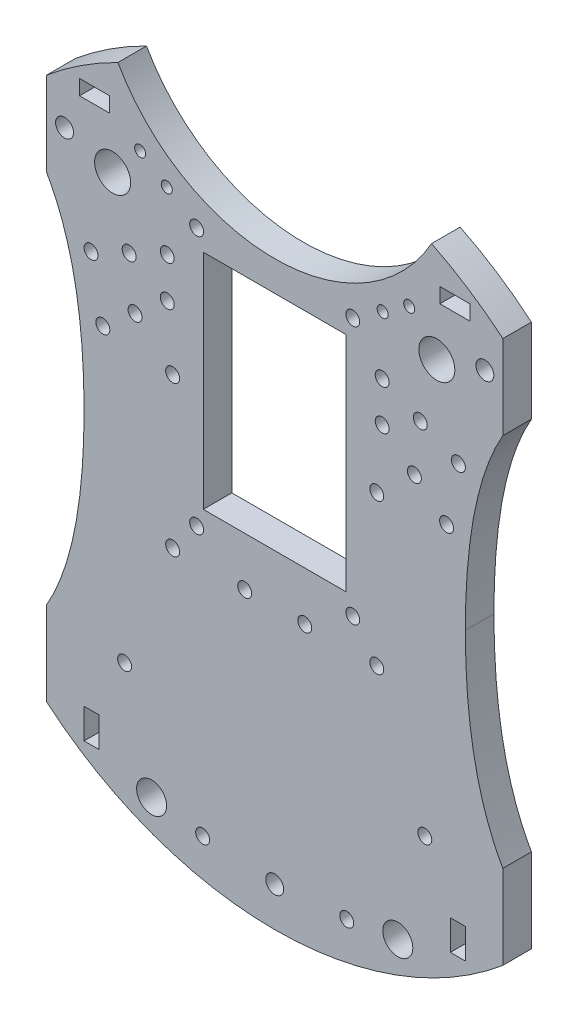
SolidWorks part; units mm, degrees
ref_plane "Front Plane" through (0, 0, 0) normal (0, 0, 1) x (1, 0, 0)
ref_plane "Top Plane" through (0, 0, 0) normal (0, 1, 0) x (1, 0, 0)
ref_plane "Right Plane" through (0, 0, 0) normal (1, 0, 0) x (0, 0, -1)
sketch "Sketch1" plane through (0, 0, 0) normal (0, 0, 1) x (1, 0, 0)
  line L0 (0, 47.9049) -> (0, -75) construction
  line L1 (-48.26, 0) -> (48.26, 0) construction
  line L5 (-48.26, 57.4106) -> (-48.26, -57.4106)
  line L22 (48.26, 57.4106) -> (48.26, -57.4106)
  arc A0 (-33.1727, 67.265) -> (-48.26, 57.4106) centre (0, 0) ccw
  arc A1 (-33.1727, 67.265) -> (33.1727, 67.265) centre (0, 86.0049) ccw
  circle A2 centre (0, -66.675) radius 1.8987
  circle A3 centre (-44.45, 49.6966) radius 1.8987
  circle A4 centre (44.45, 49.6966) radius 1.8986
  circle A5 centre (-21.59, -15.875) radius 1.4732
  circle A6 centre (-6.35, -15.875) radius 1.4732
  circle A7 centre (6.35, -15.875) radius 1.4732
  circle A8 centre (-15.24, -65.475) radius 1.4732
  circle A9 centre (15.24, -65.475) radius 1.4732
  circle A12 centre (21.59, -15.875) radius 1.4732
  circle A13 centre (6.35, 15.875) radius 1.4732
  circle A14 centre (-6.35, 15.875) radius 1.4732
  circle A15 centre (21.59, 15.875) radius 1.4732
  circle A18 centre (-21.59, 15.875) radius 1.4732
  arc A29 (-48.26, -57.4106) -> (48.26, -57.4106) centre (0, 0) ccw
  arc A30 (48.26, 57.4106) -> (33.1727, 67.265) centre (0, 0) ccw
  circle A31 centre (0, 0) radius 66.675 construction
  point P1 (-48.26, 0)
  point P50 (0, -65.475)
  dimension "D1" = 150
  dimension "D8" = 3.7973
  dimension "D12" = 133.35
  dimension "D11" = 3.7973
  dimension "D20" = 26.67
  dimension "D19" = 2.9464
  dimension "D9" = 2.9464
  dimension "D2" = 66.3453
  dimension "D3" = 38.1
  dimension "D4" = 44.45
  dimension "D6" = 48.26
  dimension "D7" = 0
  dimension "D13" = 15.875
  dimension "D14" = 9.525
  dimension "D18" = 0
  dimension "D23" = 15.24
  dimension "D10" = 15.24
extrude "Boss-Extrude3" add sketch "Sketch1" along normal blind 6.0452
sketch "Sketch7" plane through (0, 0, 6.0452) normal (0, 0, 1) x (1, 0, 0)
  line L0 (-34.925, -41.98) -> (34.925, -41.98) construction
  line L1 (-34.925, -61.03) -> (-34.925, -22.93) construction
  line L2 (-34.925, -61.03) -> (34.925, -61.03) construction
  line L3 (34.925, -61.03) -> (34.925, -22.93) construction
  line L4 (-34.925, -22.93) -> (34.925, -22.93) construction
  line L5 (0, -61.03) -> (0, -22.93) construction
  line L6 (-28.575, -55.7849) -> (-28.575, -28.1751) construction
  line L7 (-28.575, -55.7849) -> (28.575, -55.7849) construction
  line L8 (28.575, -55.7849) -> (28.575, -28.1751) construction
  line L9 (-28.575, -28.1751) -> (28.575, -28.1751) construction
  line L10 (-28.575, -55.7849) -> (28.575, -28.1751) construction
  line L11 (28.575, -55.7849) -> (-28.575, -28.1751) construction
  line L12 (0, 47.9049) -> (0, -75) construction
  circle A0 centre (-31.75, -41.98) radius 1.4732
  circle A1 centre (31.75, -41.98) radius 1.4732
  arc A2 (-33.1727, 67.265) -> (33.1727, 67.265) centre (0, 86.0049) ccw construction
  arc A3 (-48.26, -57.4106) -> (48.26, -57.4106) centre (0, 0) ccw construction
  point P0 (0, -41.98)
  dimension "D1" = 69.85
  dimension "D2" = 57.15
  dimension "D3" = 27.6098
  dimension "D4" = 3.175
  dimension "D5" = 38.1
  dimension "D6" = 33.02
extrude "Cut-Extrude2" cut sketch "Sketch7" against normal through all
sketch "Sketch9" plane through (0, 0, 6.0452) normal (0, 0, 1) x (1, 0, 0)
  line L1 (-15.113, 41.5549) -> (15.113, 41.5549)
  line L2 (-15.113, 41.5549) -> (-15.113, -5.5621)
  line L3 (-15.113, -5.5621) -> (15.113, -5.5621)
  line L4 (15.113, 41.5549) -> (15.113, -5.5621)
  line L5 (-15.113, 17.9964) -> (15.113, 17.9964) construction
  line L6 (0, 47.8414) -> (0, -11.8486) construction
  line L7 (0, 47.9049) -> (0, -75) construction
  line L8 (-19.05, 47.8414) -> (19.05, 47.8414) construction
  line L9 (-19.05, 47.8414) -> (-19.05, -11.8486) construction
  line L10 (-19.05, -11.8486) -> (19.05, -11.8486) construction
  line L11 (19.05, 47.8414) -> (19.05, -11.8486) construction
  line L12 (-19.05, 17.9964) -> (19.05, 17.9964) construction
  arc A1 (-33.1727, 67.265) -> (33.1727, 67.265) centre (0, 86.0049) ccw construction
  arc A2 (-48.26, -57.4106) -> (48.26, -57.4106) centre (0, 0) ccw construction
  circle A3 centre (-16.51, 45.3014) radius 1.4732
  circle A4 centre (16.51, 45.3014) radius 1.4732
  circle A5 centre (-16.51, -9.3086) radius 1.4732
  circle A6 centre (16.51, -9.3086) radius 1.4732
  point P6 (0, 17.9964)
  dimension "D6" = 2.9464
  dimension "D7" = 5.08
  dimension "D8" = 5.08
  dimension "D1" = 30.226
  dimension "D2" = 47.117
  dimension "D3" = 6.35
  dimension "D4" = 59.69
  dimension "D5" = 38.1
extrude "Cut-Extrude3" cut sketch "Sketch9" against normal blind 14.732
sketch "Sketch10" plane through (0, 0, 6.0452) normal (0, 0, 1) x (1, 0, 0)
  line L0 (0, 47.9049) -> (0, -75) construction
  line L2 (-41.275, 60.2874) -> (-34.925, 60.2874)
  line L3 (-41.275, 60.2874) -> (-41.275, 57.1124)
  line L4 (-41.275, 57.1124) -> (-34.925, 57.1124)
  line L5 (-34.925, 60.2874) -> (-34.925, 57.1124)
  line L6 (-41.275, 60.2874) -> (-34.925, 57.1124) construction
  line L7 (-41.275, 57.1124) -> (-34.925, 60.2874) construction
  line L8 (34.925, 60.2874) -> (34.925, 57.1124)
  line L9 (41.275, 60.2874) -> (34.925, 60.2874)
  line L10 (41.275, 60.2874) -> (41.275, 57.1124)
  line L11 (41.275, 57.1124) -> (34.925, 57.1124)
  line L13 (-40.3225, -54.2356) -> (-37.1475, -54.2356)
  line L14 (-40.3225, -54.2356) -> (-40.3225, -60.5856)
  line L15 (-40.3225, -60.5856) -> (-37.1475, -60.5856)
  line L16 (-37.1475, -54.2356) -> (-37.1475, -60.5856)
  line L17 (-40.3225, -54.2356) -> (-37.1475, -60.5856) construction
  line L18 (-40.3225, -60.5856) -> (-37.1475, -54.2356) construction
  line L19 (40.3225, -60.5856) -> (37.1475, -54.2356) construction
  line L20 (40.3225, -54.2356) -> (37.1475, -60.5856) construction
  line L21 (37.1475, -54.2356) -> (37.1475, -60.5856)
  line L22 (40.3225, -60.5856) -> (37.1475, -60.5856)
  line L23 (40.3225, -54.2356) -> (40.3225, -60.5856)
  line L24 (40.3225, -54.2356) -> (37.1475, -54.2356)
  arc A0 (-33.1727, 67.265) -> (33.1727, 67.265) centre (0, 86.0049) ccw construction
  arc A1 (-48.26, -57.4106) -> (48.26, -57.4106) centre (0, 0) ccw construction
  circle A3 centre (-26.035, -63.7606) radius 3.175
  circle A4 centre (26.035, -63.7606) radius 3.175
  circle A5 centre (-34.29, 46.5848) radius 3.81
  circle A6 centre (34.29, 46.5848) radius 3.81
  point P8 (-38.1, 58.6999)
  point P19 (-38.735, -57.4106)
  point P30 (38.735, -57.4106)
  dimension "D8" = 6.35
  dimension "D10" = 7.62
  dimension "D1" = 3.175
  dimension "D2" = 6.35
  dimension "D3" = 38.1
  dimension "D4" = 10.795
  dimension "D5" = 38.735
  dimension "D6" = 0
  dimension "D7" = 12.7
  dimension "D9" = 12.7
  dimension "D11" = 6.35
  dimension "D12" = 34.29
extrude "Cut-Extrude4" cut sketch "Sketch10" against normal up to surface (6.0452 mm away) up to face at (17.9832, -9.3086, 0)
sketch "Sketch11" plane through (0, 0, 6.0452) normal (0, 0, 1) x (1, 0, 0)
  line L0 (-62.6209, 41.275) -> (-62.6209, -41.275) construction
  circle A0 centre (0, 0) radius 75 construction
  dimension "D2" = 150
  dimension "D1" = 82.55
sketch "Sketch12" plane through (0, 0, 6.0452) normal (0, 0, 1) x (1, 0, 0)
  line L0 (0, 47.9049) -> (0, -74.9486) construction
  line L1 (0, 47.9049) -> (48.26, 25.4009) construction
  line L2 (48.26, -57.4106) -> (48.26, 57.4106) construction
  line L3 (15.113, -5.5621) -> (15.113, 41.5549) construction
  line L4 (0, 47.9049) -> (48.26, 7.4099) construction
  arc A0 (-33.1727, 67.265) -> (33.1727, 67.265) centre (0, 86.0049) ccw construction
  circle A1 centre (22.733, 37.3043) radius 1.4732
  circle A2 centre (30.7901, 33.5472) radius 1.4732
  circle A3 centre (38.8472, 29.7902) radius 1.4732
  circle A5 centre (22.733, 28.8296) radius 1.4732
  circle A6 centre (29.5431, 23.1152) radius 1.4732
  circle A7 centre (36.3533, 17.4009) radius 1.4732
  circle A8 centre (43.1634, 11.6865) radius 1.4732
  circle A9 centre (-43.1634, 11.6865) radius 1.4732
  circle A10 centre (-36.3533, 17.4009) radius 1.4732
  circle A11 centre (-29.5431, 23.1152) radius 1.4732
  circle A12 centre (-22.733, 28.8296) radius 1.4732
  circle A14 centre (-38.8472, 29.7902) radius 1.4732
  circle A15 centre (-30.7901, 33.5472) radius 1.4732
  circle A16 centre (-22.733, 37.3043) radius 1.4732
  circle A17 centre (46.9042, 26.0331) radius 1.4732 [skipped]
  dimension "D2" = 2.9464
  dimension "D5" = 8.89
  dimension "D1" = 65
  dimension "D3" = 7.62
  dimension "D6" = 50
  dimension "D8" = 8.89
  dimension "D4" = 4
  dimension "D7" = 4
extrude "Cut-Extrude5" cut sketch "Sketch12" against normal up to surface (6.0452 mm away) up to face at (38.1, 46.5848, 0)
sketch "Sketch13" plane through (0, 0, 6.0452) normal (0, 0, 1) x (1, 0, 0)
  line L0 (0, 47.9049) -> (0, -75) construction
  line L7 (-22.9461, 55.5249) -> (-26.5812, 50.1335) construction
  line L8 (-28.2533, 59.1032) -> (-17.6389, 51.9466) construction
  line L9 (-28.2533, 59.1032) -> (-31.8884, 53.7117) construction
  line L10 (-31.8884, 53.7117) -> (-21.274, 46.5552) construction
  line L11 (-17.6389, 51.9466) -> (-21.274, 46.5552) construction
  line L12 (-28.2533, 59.1032) -> (-21.274, 46.5552) construction
  line L13 (-31.8884, 53.7117) -> (-17.6389, 51.9466) construction
  line L14 (15.113, 41.5549) -> (-15.113, 41.5549) construction
  circle A0 centre (0, 0) radius 75 construction
  circle A1 centre (22.8325, 49.6278) radius 1.1684
  circle A2 centre (-22.8325, 49.6278) radius 1.1684
  circle A3 centre (-28.4556, 53.4191) radius 1.1684
  arc A6 (-33.1727, 67.265) -> (33.1727, 67.265) centre (0, 86.0049) ccw construction
  circle A7 centre (28.4556, 53.4191) radius 1.1684
  point P11 (-24.7637, 52.8292)
  dimension "D4" = 2.3368
  dimension "D5" = 1.6764
  dimension "D6" = 3.3909
  dimension "D7" = 6.5024
  dimension "D8" = 12.8016
  dimension "D9" = 13.97
  dimension "D10" = 56.011
extrude "Cut-Extrude6" cut sketch "Sketch13" against normal up to surface (6.0452 mm away) up to face at (-21.2598, 37.3043, 0)
sketch "Sketch14" plane through (0, 0, 6.0452) normal (0, 0, 1) x (1, 0, 0)
  line L0 (0, 47.9049) -> (0, -75) construction
  line L1 (-48.26, 0) -> (48.26, 0) construction
  line L2 (-48.26, 57.4106) -> (-48.26, -57.4106) construction
  line L3 (48.26, -57.4106) -> (48.26, 57.4106) construction
  line L4 (-48.26, 39.6306) -> (-48.26, -39.6306)
  line L5 (-31.417, 10.4577) -> (-63.167, 65.4503) construction
  line L6 (48.26, 39.6306) -> (48.26, -39.6306)
  arc A0 (-33.1727, 67.265) -> (33.1727, 67.265) centre (0, 86.0049) ccw construction
  circle A1 centre (0, 0) radius 75 construction
  spline S0 degree 2 poles (-48.26, 39.6306) (-40.3225, 25.8824) (-40.3225, 0) knots 0 0 0 1 1 1
  spline S1 degree 2 poles (-48.26, -39.6306) (-40.3225, -25.8824) (-40.3225, 0) knots 0 0 0 1 1 1
  spline S2 degree 2 poles (48.26, -39.6306) (40.3225, -25.8824) (40.3225, 0) knots 0 0 0 1 1 1
  spline S3 degree 2 poles (48.26, 39.6306) (40.3225, 25.8824) (40.3225, 0) knots 0 0 0 1 1 1
  dimension "D2" = 31.75
  dimension "D1" = 17.78
  dimension "D3" = 30
extrude "Cut-Extrude7" cut sketch "Sketch14" against normal up to surface (6.0452 mm away) up to face at (-27.2872, 53.4191, 0)
